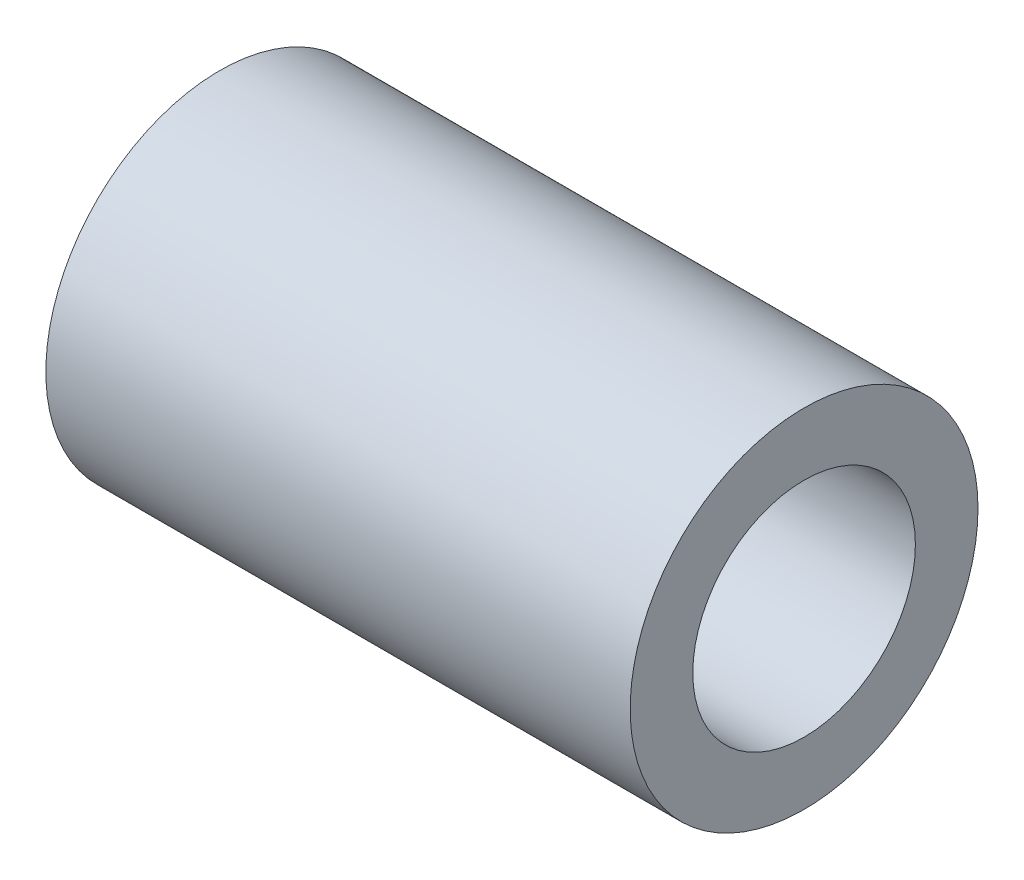
SolidWorks part; units mm, degrees
ref_plane "前视基准面" through (0, 0, 0) normal (0, 0, 1) x (1, 0, 0)
ref_plane "上视基准面" through (0, 0, 0) normal (0, 1, 0) x (1, 0, 0)
ref_plane "右视基准面" through (0, 0, 0) normal (1, 0, 0) x (0, 0, -1)
other "Configuration Table"
sketch "草图1" plane through (0, 0, 0) normal (1, 0, 0) x (0, 0, -1)
  circle A0 centre (0, 0) radius 2.5
  circle A1 centre (0, 0) radius 1.6
  dimension "D1" = 5
  dimension "D2" = 3.2
extrude "凸台-拉伸1" add sketch "草图1" along normal blind 8.4
